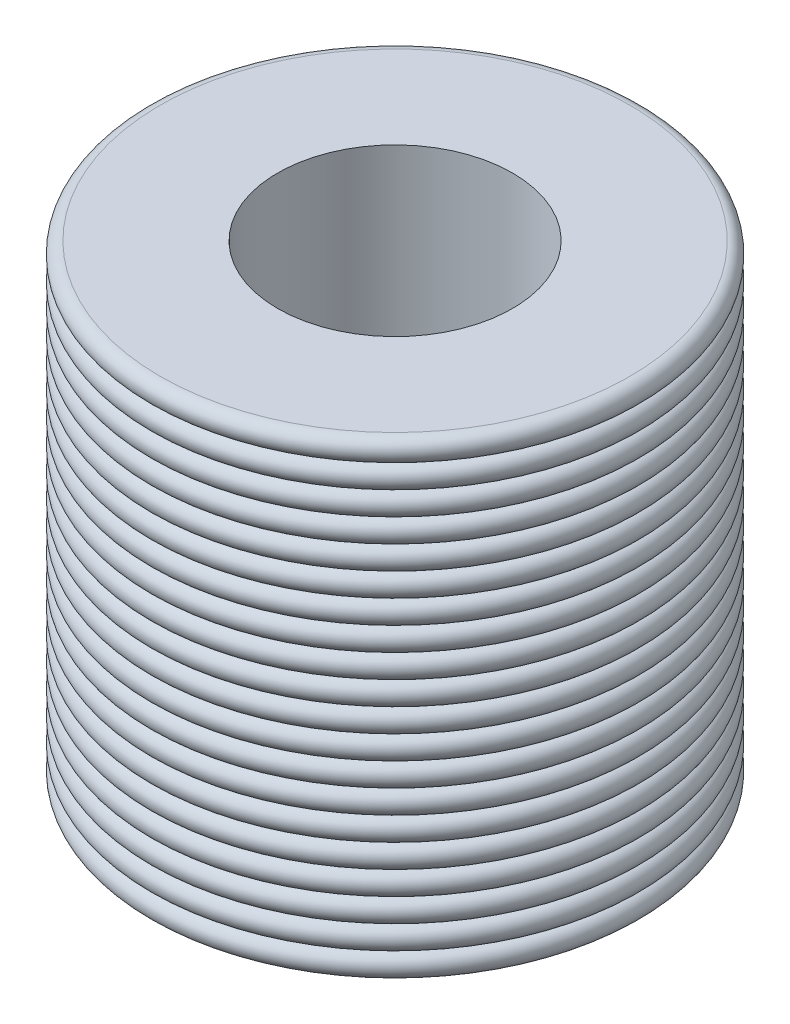
SolidWorks part; units mm, degrees
material "Copper"
ref_plane "Front Plane" through (0, 0, 0) normal (0, 0, 1) x (1, 0, 0)
ref_plane "Top Plane" through (0, 0, 0) normal (0, 1, 0) x (1, 0, 0)
ref_plane "Right Plane" through (0, 0, 0) normal (1, 0, 0) x (0, 0, -1)
sketch "Sketch1" plane through (0, 0, 0) normal (1, 0, 0) x (0, 0, -1)
  line L0 (0, 24.6629) -> (0, -25.6742) construction
  line L1 (-10, 23.6517) -> (-10, -16.3483)
  line L2 (-10, 23.6517) -> (-20, 23.6517)
  line L3 (-20, 23.6517) -> (-20, -16.3483) construction
  line L4 (-10, -16.3483) -> (-20, -16.3483)
  arc A0 (-20, 23.6517) -> (-20, 21.6517) centre (-20, 22.6517) ccw
  arc A1 (-20, 21.6517) -> (-20, 19.6517) centre (-20, 20.6517) ccw
  arc A2 (-20, 19.6517) -> (-20, 17.6517) centre (-20, 18.6517) ccw
  arc A3 (-20, 17.6517) -> (-20, 15.6517) centre (-20, 16.6517) ccw
  arc A4 (-20, 15.6517) -> (-20, 13.6517) centre (-20, 14.6517) ccw
  arc A5 (-20, 13.6517) -> (-20, 11.6517) centre (-20, 12.6517) ccw
  arc A6 (-20, 11.6517) -> (-20, 9.6517) centre (-20, 10.6517) ccw
  arc A7 (-20, 9.6517) -> (-20, 7.6517) centre (-20, 8.6517) ccw
  arc A8 (-20, 7.6517) -> (-20, 5.6517) centre (-20, 6.6517) ccw
  arc A9 (-20, 5.6517) -> (-20, 3.6517) centre (-20, 4.6517) ccw
  arc A10 (-20, 3.6517) -> (-20, 1.6517) centre (-20, 2.6517) ccw
  arc A11 (-20, 1.6517) -> (-20, -0.3483) centre (-20, 0.6517) ccw
  arc A12 (-20, -0.3483) -> (-20, -2.3483) centre (-20, -1.3483) ccw
  arc A13 (-20, -2.3483) -> (-20, -4.3483) centre (-20, -3.3483) ccw
  arc A14 (-20, -4.3483) -> (-20, -6.3483) centre (-20, -5.3483) ccw
  arc A15 (-20, -6.3483) -> (-20, -8.3483) centre (-20, -7.3483) ccw
  arc A16 (-20, -8.3483) -> (-20, -10.3483) centre (-20, -9.3483) ccw
  arc A17 (-20, -10.3483) -> (-20, -12.3483) centre (-20, -11.3483) ccw
  arc A18 (-20, -12.3483) -> (-20, -14.3483) centre (-20, -13.3483) ccw
  arc A19 (-20, -14.3483) -> (-20, -16.3483) centre (-20, -15.3483) ccw
  dimension "D3" = 1
  dimension "D1" = 20
  dimension "D2" = 40
  dimension "D4" = 10
revolve "Revolve1" add sketch "Sketch1" angle 360 about L0
